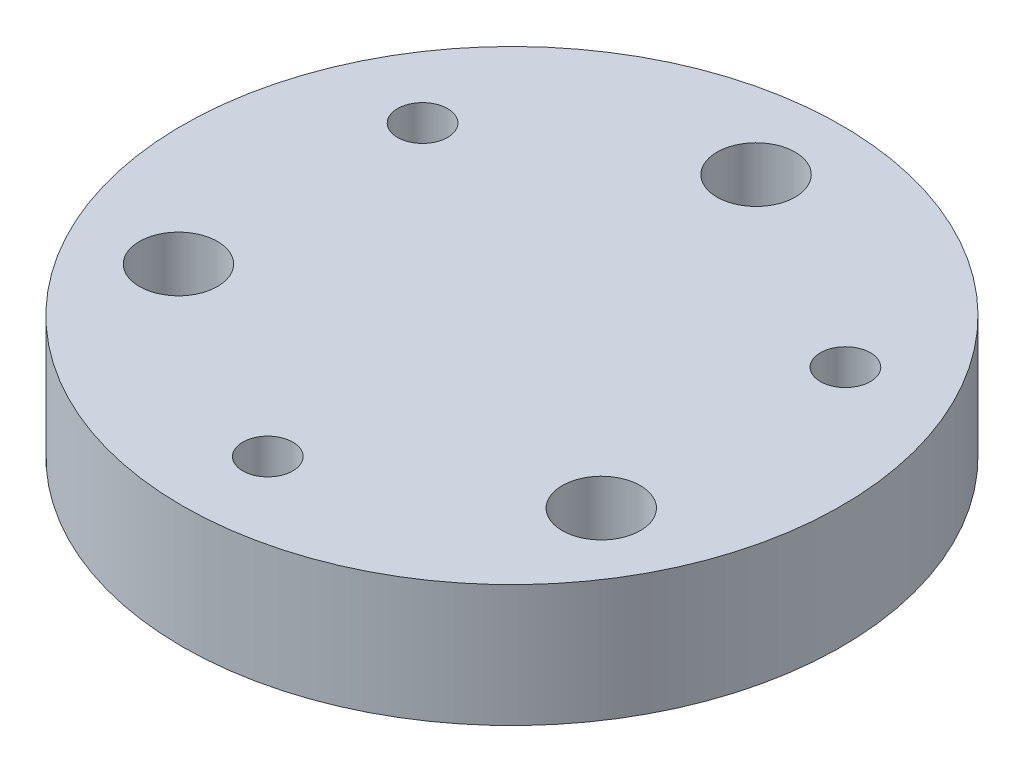
SolidWorks part; units mm, degrees
material "5052-H32"
ref_plane "前视基准面" through (0, 0, 0) normal (0, 0, 1) x (1, 0, 0)
ref_plane "上视基准面" through (0, 0, 0) normal (0, 1, 0) x (1, 0, 0)
ref_plane "右视基准面" through (0, 0, 0) normal (1, 0, 0) x (0, 0, -1)
other "Configuration Table"
sketch "草图1" plane through (0, 0, 0) normal (0, 1, 0) x (1, 0, 0)
  line L0 (0, 10) -> (0, 0) construction
  line L1 (0, 0) -> (8.6603, 5) construction
  circle A0 centre (0, 0) radius 13.5
  circle A1 centre (0, 0) radius 10 construction
  circle A2 centre (0, 10) radius 1.6
  circle A3 centre (8.6603, -5) radius 1.6
  circle A4 centre (-8.6603, -5) radius 1.6
  circle A5 centre (8.6603, 5) radius 1.025
  circle A6 centre (0, -10) radius 1.025
  circle A7 centre (-8.6603, 5) radius 1.025
  point P13 (0, 0)
  point P20 (0, 0)
  dimension "D1" = 27
  dimension "D2" = 20
  dimension "D3" = 3.2
  dimension "D5" = 2.05
  dimension "D4" = 60
extrude "凸台-拉伸1" add sketch "草图1" along normal blind 5
